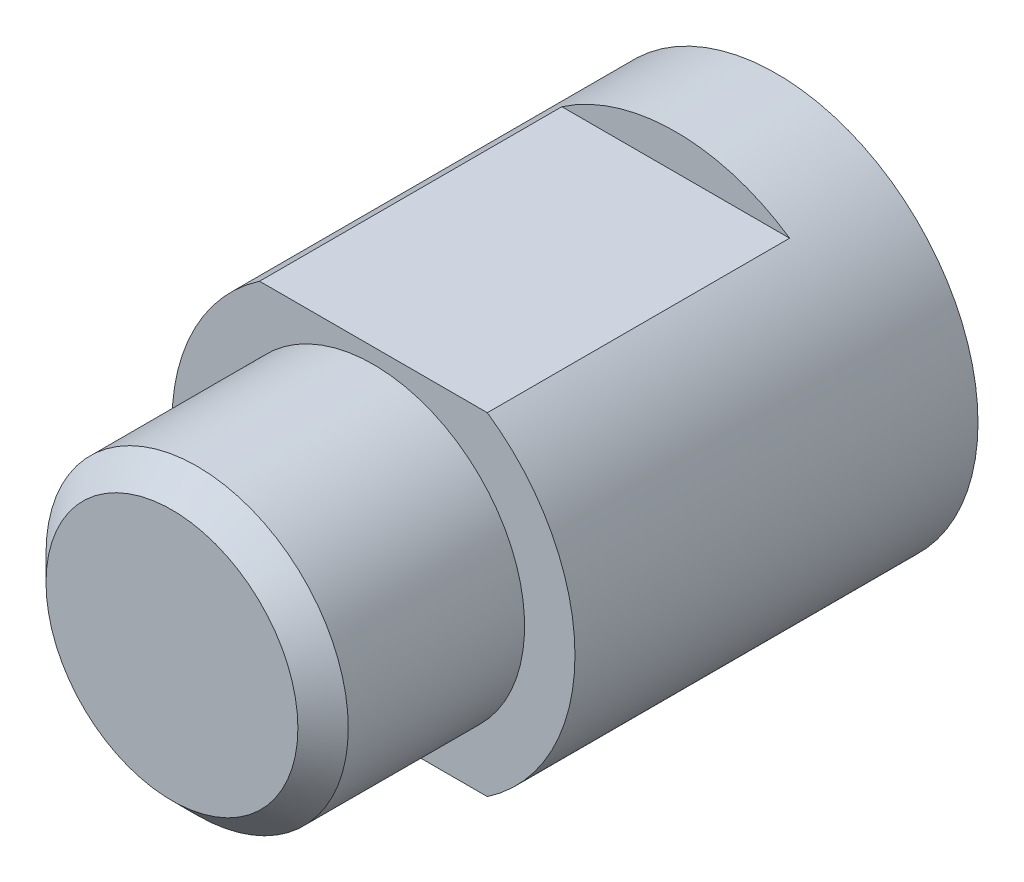
SolidWorks part; units mm, degrees
material "SKD11淬火HRC56-60"
ref_plane "前基準面" through (0, 0, 0) normal (0, 0, 1) x (1, 0, 0)
ref_plane "上基準面" through (0, 0, 0) normal (0, 1, 0) x (1, 0, 0)
ref_plane "右基準面" through (0, 0, 0) normal (1, 0, 0) x (0, 0, -1)
sketch "草图1" plane through (0, 0, 0) normal (0, 0, 1) x (1, 0, 0)
  circle A0 centre (0, 0) radius 3
  dimension "D1" = 6
extrude "凸台-拉伸1" add sketch "草图1" along normal blind 4
chamfer "倒角1" distance 0.5 angle 45 1 edges at (3, 0, 4)
sketch "草图4" plane through (0, 0, 0) normal (0, 0, -1) x (-1, 0, 0)
  circle A0 centre (0, 0) radius 4
  dimension "D1" = 8
extrude "凸台-拉伸2" add sketch "草图4" along normal blind 8
hole_wizard "M4 螺纹孔2" positions "草图6" profile "草图5" tap size "M4" standard "ISO"
sketch "草图6" plane through (0, 0, -8) normal (0, 0, -1) x (-1, 0, 0)
  point P0 (0, 0)
sketch "草图5" plane through (0, 0, -8) normal (1, 0, 0) x (0, 1, 0)
  line L0 (0, 0) -> (0, 11.0914)
  line L1 (0, 11.0914) -> (1.65, 10.1)
  line L2 (1.65, 10.1) -> (1.65, 0)
  line L5 (1.65, 0) -> (0, 0)
  line L10 (0, 11.0914) -> (-1.65, 10.1) construction
  line L11 (0, -6.35) -> (0, 107.95) construction
  dimension "螺纹孔钻头直径" = 3.3
  dimension "螺纹孔钻头深度" = 10.1
  dimension "导头角度" = 118
cosmetic thread "孔螺蚊线2" parameters "D1"=8, "D2"=4
sketch "草图7" plane through (0, 0, 0) normal (1, 0, 0) x (0, 0, -1)
  line L0 (8, 0) -> (-8.9636, 0) construction
  line L1 (-0.666, 5.74) -> (6, 5.74)
  line L2 (-0.666, 5.74) -> (-0.666, 3.3)
  line L3 (-0.666, 3.3) -> (6, 3.3)
  line L4 (6, 5.74) -> (6, 3.3)
  line L5 (8, -4) -> (8, 4) construction
  line L6 (6, -5.74) -> (6, -3.3)
  line L7 (-0.666, -3.3) -> (6, -3.3)
  line L8 (-0.666, -5.74) -> (-0.666, -3.3)
  line L9 (-0.666, -5.74) -> (6, -5.74)
  dimension "D1" = 6.6
  dimension "D2" = 2
  dimension "D3" = 6.666
extrude "切除-拉伸1" cut sketch "草图7" against normal through all and the other way through all
